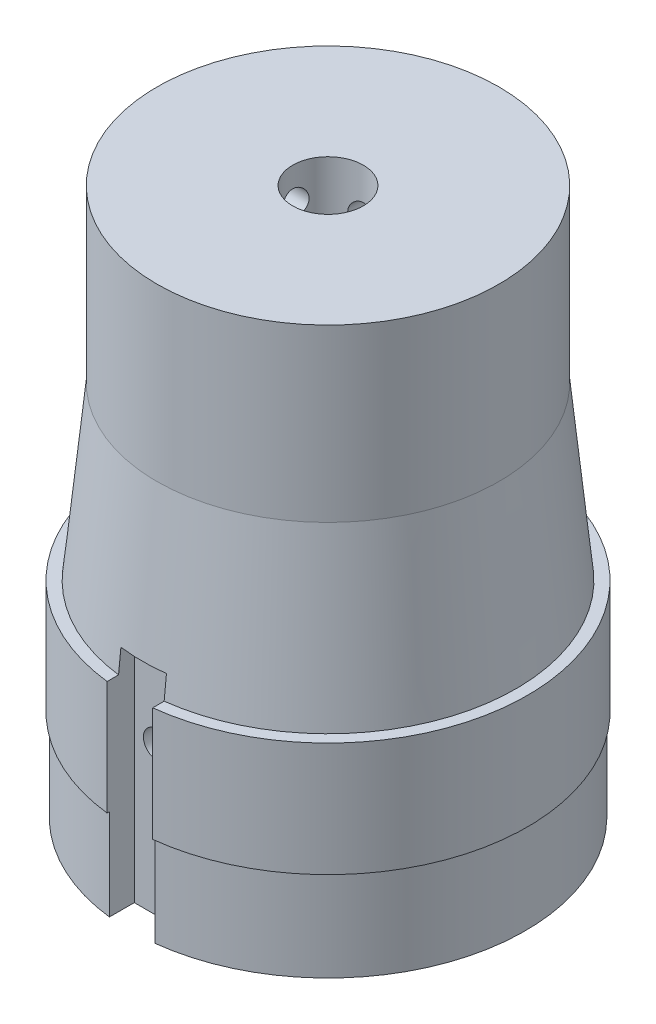
SolidWorks part; units mm, degrees
ref_plane "Alzado" through (0, 0, 0) normal (0, 0, 1) x (1, 0, 0)
ref_plane "Planta" through (0, 0, 0) normal (0, 1, 0) x (1, 0, 0)
ref_plane "Vista lateral" through (0, 0, 0) normal (1, 0, 0) x (0, 0, -1)
sketch "Croquis1" plane through (0, 0, 0) normal (0, 0, 1) x (1, 0, 0)
  line L0 (0, 40) -> (15, 40)
  line L1 (15, 40) -> (15, 25)
  line L2 (16.5, 10) -> (17.5, 10)
  line L3 (17.5, 10) -> (17.5, 0)
  line L4 (17.5, 0) -> (0, 0)
  line L5 (0, 0) -> (0, 40)
  line L6 (15, 25) -> (16.5, 10)
  line L7 (0, 63.3471) -> (0, -32.7037) construction
  line L8 (0, 0) -> (17.3, 0)
  line L9 (0, 0) -> (0, -8)
  line L10 (0, -8) -> (17.3, -8)
  line L11 (17.3, 0) -> (17.3, -8)
  line L13 (0, 24) -> (3.1, 24)
  line L14 (0, 24) -> (0, 40)
  line L15 (0, 40) -> (3.1, 40)
  line L16 (3.1, 24) -> (3.1, 40)
  point P16 (0, 0)
  dimension "D1" = 40
  dimension "D2" = 17.5
  dimension "D3" = 10
  dimension "D4" = 15
  dimension "D5" = 1
  dimension "D6" = 15
  dimension "D7" = 8
  dimension "D8" = 17.3
  dimension "D9" = 16
  dimension "D10" = 3.1
revolve "Revolucion Cuerpo" add sketch "Croquis1" angle 360 about L7
sketch "Croquis2" plane through (0, -8, 0) normal (0, -1, 0) x (1, 0, 0)
  line L0 (0, 48.0928) -> (0, -50.5638) construction
  line L2 (-2, 18) -> (2, 18)
  line L3 (-2, 18) -> (-2, 15)
  line L4 (-2, 15) -> (2, 15)
  line L5 (2, 18) -> (2, 15)
  dimension "D1" = 4
  dimension "D2" = 3
  dimension "D3" = 15
sketch "Croquis3" plane through (0, -8, 0) normal (0, -1, 0) x (1, 0, 0)
  circle A0 centre (0, 0) radius 2.5
  dimension "D1" = 5
extrude "Cortar-Extruir3" cut sketch "Croquis2" against normal blind 20
extrude "Cortar-Extruir2" cut sketch "Croquis3" against normal blind 10
sketch "Croquis4" plane through (0, 0, 0) normal (0, 0, 1) x (1, 0, 0)
  line L0 (0, 0) -> (0, 40) construction
  circle A0 centre (0, 28) radius 1.15
  circle A1 centre (0, 36) radius 1.15
  dimension "D1" = 2.3
  dimension "D2" = 12
  dimension "D3" = 8
extrude "Cortar-Extruir4" cut sketch "Croquis4" against normal blind 20
sketch "Croquis5" plane through (0, 0, 0) normal (1, 0, 0) x (0, 0, -1)
  line L0 (0, 40) -> (0, 25) construction
  line L2 (15, 40) -> (-15, 40) construction
  circle A0 centre (0, 29) radius 1.2
  circle A1 centre (0, 37) radius 1.2
  dimension "D1" = 2.4
  dimension "D2" = 11
  dimension "D3" = 8
extrude "Cortar-Extruir5" cut sketch "Croquis5" against normal blind 20
sketch "Croquis8" plane through (0, 0, 15) normal (0, 0, 1) x (1, 0, 0)
  line L0 (0, 0) -> (0, 40) construction
  line L1 (17.5, 0) -> (0, 0) construction
  circle A0 centre (0, 5) radius 1.2
  point P6 (0, 0)
  dimension "D1" = 2.4
  dimension "D2" = 5
extrude "Cortar-Extruir6" cut sketch "Croquis8" against normal blind 10
